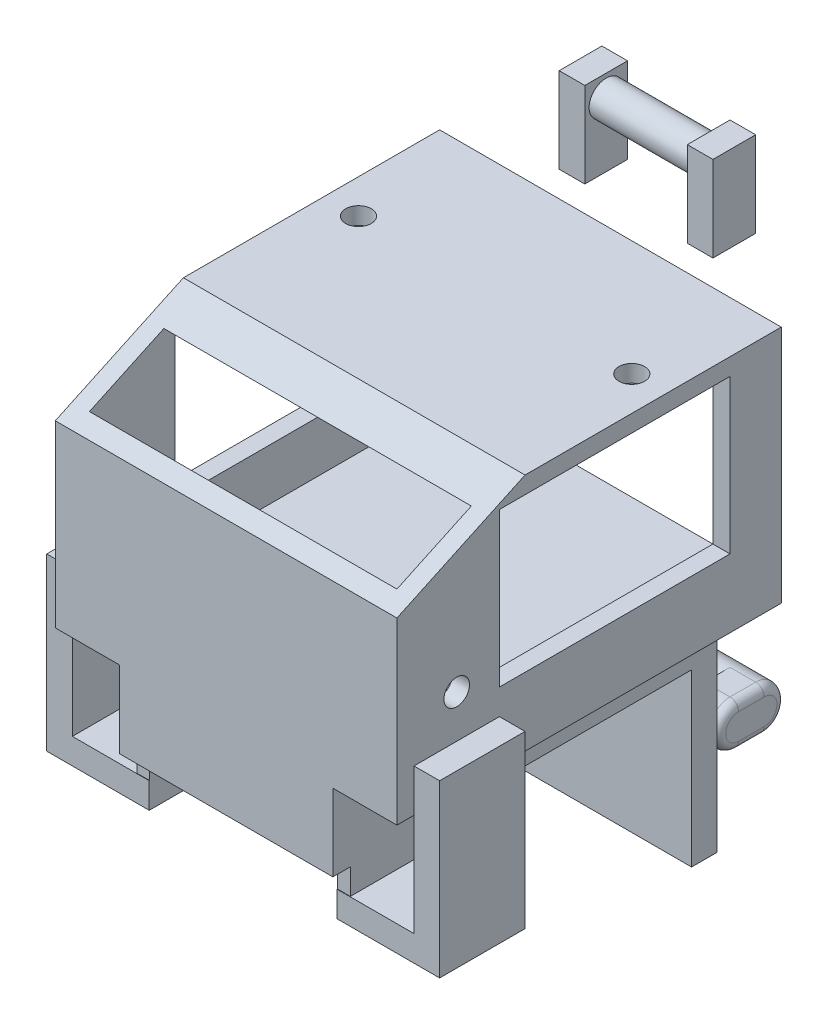
SolidWorks part; units mm, degrees
ref_plane "正面" through (0, 0, 0) normal (0, 0, 1) x (1, 0, 0)
ref_plane "平面" through (0, 0, 0) normal (0, 1, 0) x (1, 0, 0)
ref_plane "右側面" through (0, 0, 0) normal (1, 0, 0) x (0, 0, -1)
sketch "ｽｹｯﾁ1" plane through (0, 0, 0) normal (0, 1, 0) x (1, 0, 0)
  line L1 (0, 0) -> (25, 0)
  line L2 (0, 0) -> (0, 42)
  line L3 (0, 42) -> (25, 42)
  line L4 (25, 0) -> (25, 42)
  dimension "D1" = 25
  dimension "D2" = 42
extrude "ﾎﾞｽ - 押し出し1" add sketch "ｽｹｯﾁ1" along normal blind 9
sketch "ｽｹｯﾁ2" plane through (0, 0, -42) normal (0, 0, -1) x (-1, 0, 0)
  line L1 (-25, 9) -> (0, 9)
  line L2 (-25, 9) -> (-25, -20)
  line L3 (-25, -20) -> (0, -20)
  line L4 (0, 9) -> (0, -20)
  dimension "D1" = 29
extrude "ﾎﾞｽ - 押し出し2" add sketch "ｽｹｯﾁ2" along normal blind 3
sketch "ｽｹｯﾁ3" plane through (0, 9, 0) normal (0, 1, 0) x (1, 0, 0)
  line L1 (-7.5, 0) -> (32.5, 0)
  line L2 (-7.5, 0) -> (-7.5, 45)
  line L3 (-7.5, 45) -> (32.5, 45)
  line L4 (32.5, 0) -> (32.5, 45)
  line L5 (0, 0) -> (25, 0) construction
  line L6 (0, 45) -> (25, 45) construction
  line L7 (0, 45) -> (0, 0) construction
  dimension "D1" = 40
  dimension "D2" = 7.5
extrude "ﾎﾞｽ - 押し出し3" add sketch "ｽｹｯﾁ3" along normal blind 28
sketch "ｽｹｯﾁ4" plane through (0, 0, -45) normal (0, 0, -1) x (-1, 0, 0)
  line L0 (-32.5, 37) -> (7.5, 37) construction
  line L1 (5.5, 35) -> (-30.5, 35)
  line L2 (5.5, 35) -> (5.5, 11)
  line L3 (5.5, 11) -> (-30.5, 11)
  line L4 (-30.5, 35) -> (-30.5, 11)
  line L5 (7.5, 37) -> (7.5, 9) construction
  line L6 (-32.5, 37) -> (-32.5, 9) construction
  line L7 (0, 9) -> (7.5, 9) construction
  dimension "D1" = 2
  dimension "D2" = 2
  dimension "D3" = 2
  dimension "D4" = 2
extrude "ｶｯﾄ - 押し出し1" cut sketch "ｽｹｯﾁ4" against normal blind 43
sketch "ｽｹｯﾁ6" plane through (32.5, 0, 0) normal (1, 0, 0) x (0, 0, -1)
  line L0 (42, 0) -> (42, -20) construction
  line L1 (2, -6) -> (12, -6)
  line L2 (2, -6) -> (2, 14)
  line L3 (2, 14) -> (12, 14)
  line L4 (12, -6) -> (12, 14)
  line L5 (0, 9) -> (45, 9) construction
  dimension "D1" = 30
  dimension "D2" = 20
  dimension "D3" = 10
  dimension "D4" = 15
extrude "ﾎﾞｽ - 押し出し4" add sketch "ｽｹｯﾁ6" along normal blind 3
sketch "ｽｹｯﾁ7" plane through (0, -6, 0) normal (0, -1, 0) x (1, 0, 0)
  line L0 (35.5, -2) -> (32.5, -2) construction
  line L1 (32.5, -12) -> (23.5, -12)
  line L2 (32.5, -12) -> (32.5, -2)
  line L3 (32.5, -2) -> (23.5, -2)
  line L4 (23.5, -12) -> (23.5, -2)
  dimension "D1" = 9
extrude "ﾎﾞｽ - 押し出し5" add sketch "ｽｹｯﾁ7" against normal blind 3
ref_plane "平面1" through (12.5, 0, 0) normal (1, 0, 0) x (0, 0, -1)
mirror "ﾐﾗｰ1" about plane through (12.5, 0, 0) normal (1, 0, 0) of "ﾎﾞｽ - 押し出し4", "ﾎﾞｽ - 押し出し5"
sketch "ｽｹｯﾁ8" plane through (0, 37, 0) normal (0, 1, 0) x (1, 0, 0)
  line L0 (12.5, -15.95) -> (12.5, 15.95) construction
  line L1 (3.5, 53) -> (6.5, 53)
  line L2 (3.5, 53) -> (3.5, 48)
  line L3 (3.5, 48) -> (6.5, 48)
  line L4 (6.5, 53) -> (6.5, 48)
  line L5 (21.5, 48) -> (18.5, 48)
  line L6 (18.5, 53) -> (18.5, 48)
  line L7 (21.5, 53) -> (18.5, 53)
  line L8 (21.5, 53) -> (21.5, 48)
  line L10 (32.5, 45) -> (-7.5, 45) construction
  dimension "D1" = 5
  dimension "D2" = 3
  dimension "D3" = 12
  dimension "D4" = 8
extrude "ﾎﾞｽ - 押し出し6" add sketch "ｽｹｯﾁ8" along normal blind 10
sketch "ｽｹｯﾁ9" plane through (6.5, 0, 0) normal (1, 0, 0) x (0, 0, -1)
  line L0 (48, 47) -> (48, 37) construction
  line L1 (48, 47) -> (53, 47) construction
  circle A0 centre (50.5, 44.5) radius 2
  dimension "D1" = 4
  dimension "D2" = 2.5
  dimension "D3" = 2.5
extrude "ﾎﾞｽ - 押し出し7" add sketch "ｽｹｯﾁ9" along normal up to next (12 mm away)
sketch "ｽｹｯﾁ10" plane through (-7.5, 0, 0) normal (-1, 0, 0) x (0, 0, 1)
  line L0 (-2, 9) -> (0, 9) construction
  line L1 (0, 37) -> (0, 9) construction
  circle A0 centre (-7, 19) radius 1.5
  dimension "D1" = 3
  dimension "D2" = 10
  dimension "D3" = 7
extrude "ｶｯﾄ - 押し出し2" cut sketch "ｽｹｯﾁ10" against normal through all
sketch "ｽｹｯﾁ11" plane through (0, 0, -45) normal (0, 0, -1) x (-1, 0, 0)
  line L1 (-25, -20) -> (0, -20) construction
  line L2 (-12.5, 15.95) -> (-12.5, -15.95) construction
  circle A0 centre (-12.5, -10) radius 2.5
  dimension "D1" = 5
  dimension "D2" = 10
extrude "ﾎﾞｽ - 押し出し8" add sketch "ｽｹｯﾁ11" along normal blind 9
sketch "ｽｹｯﾁ12" plane through (12.5, 0, 0) normal (1, 0, 0) x (0, 0, -1)
  line L0 (45, -12.5) -> (45, -7.5) construction
  line L2 (45, -12.5) -> (54, -12.5) construction
  circle A0 centre (52, -10) radius 2.5
  dimension "D1" = 5
  dimension "D2" = 7
  dimension "D3" = 2.5
extrude "ﾎﾞｽ - 押し出し9" add sketch "ｽｹｯﾁ12" along normal blind 7
sketch "ｽｹｯﾁ13" plane through (19.5, 0, 0) normal (1, 0, 0) x (0, 0, -1)
  line L0 (52, -10) -> (49, -10) construction
  line L1 (52, -12.5) -> (49, -12.5)
  line L2 (52, -7.5) -> (49, -7.5)
  arc A0 (52, -12.5) -> (52, -7.5) centre (52, -10) ccw
  arc A1 (49, -7.5) -> (49, -12.5) centre (49, -10) ccw
  circle A2 centre (52, -10) radius 2.5 construction
  point P2 (50.5, -10)
  dimension "D1" = 2.5
  dimension "D2" = 3
extrude "ﾎﾞｽ - 押し出し10" add sketch "ｽｹｯﾁ13" along normal blind 4
fillet "ﾌｨﾚｯﾄ1" radius 1 4 edges at (23.5, -12.5, -50.5) (23.5, -10, -46.5) (23.5, -7.5, -50.5) (23.5, -10, -54.5)
mirror "ﾐﾗｰ2" about plane through (12.5, 0, 0) normal (1, 0, 0) of "ﾌｨﾚｯﾄ1", "ﾎﾞｽ - 押し出し10", "ﾎﾞｽ - 押し出し9"
sketch "ｽｹｯﾁ14" plane through (-7.5, 0, 0) normal (-1, 0, 0) x (0, 0, 1)
  line L0 (-15, 37) -> (0, 30)
  line L1 (-45, 37) -> (0, 37) construction
  line L2 (0, 37) -> (0, 9) construction
  line L3 (0, 30) -> (0, 37)
  line L4 (0, 37) -> (-15, 37)
  dimension "D1" = 15
  dimension "D2" = 7
extrude "ｶｯﾄ - 押し出し3" cut sketch "ｽｹｯﾁ14" against normal through all
sketch "ｽｹｯﾁ15" plane through (-7.5, 0, 0) normal (-1, 0, 0) x (0, 0, 1)
  line L0 (-45, 9) -> (-53, 37)
  line L1 (-53, 37) -> (-45, 37)
  line L2 (-45, 37) -> (-45, 9)
  dimension "D1" = 8
sketch "ｽｹｯﾁ19" plane through (30.5, 0, 0) normal (-1, 0, 0) x (0, 0, 1)
  line L0 (-10.7143, 35) -> (-45, 35) construction
  line L1 (-39, 17) -> (-12, 17)
  line L2 (-39, 17) -> (-39, 35)
  line L3 (-39, 35) -> (-12, 35)
  line L4 (-12, 17) -> (-12, 35)
  line L5 (-2, 30.9333) -> (-2, 11) construction
  dimension "D1" = 27
  dimension "D2" = 10
  dimension "D3" = 18
extrude "ｶｯﾄ - 押し出し5" cut sketch "ｽｹｯﾁ19" against normal through all both and the other way through all
sketch "ｽｹｯﾁ20" plane through (0, 37, 0) normal (0, 1, 0) x (1, 0, 0)
  line L0 (-7.5, 45) -> (-7.5, 15) construction
  line L1 (32.5, 15) -> (32.5, 45) construction
  line L2 (3.5, 48) -> (6.5, 48) construction
  line L3 (18.5, 48) -> (21.5, 48) construction
  circle A0 centre (-3.5, 31.5) radius 1.5
  circle A1 centre (28.5, 31.5) radius 1.5
  dimension "D1" = 3
  dimension "D2" = 3
  dimension "D3" = 4
  dimension "D4" = 4
  dimension "D5" = 16.5
  dimension "D6" = 16.5
extrude "ｶｯﾄ - 押し出し6" cut sketch "ｽｹｯﾁ20" against normal blind 10 and the other way through all
sketch "ｽｹｯﾁ21" plane through (0, 35, 0) normal (0, -1, 0) x (1, 0, 0)
  line L0 (-5.5, -45) -> (30.5, -45) construction
  line L1 (-5.5, -10.7143) -> (-5.5, -12) construction
  line L2 (22.5, -45) -> (19.5, -45)
  line L3 (22.5, -45) -> (22.5, -40)
  line L4 (22.5, -40) -> (19.5, -40)
  line L5 (19.5, -45) -> (19.5, -40)
  line L6 (5.5, -45) -> (2.5, -45)
  line L7 (5.5, -45) -> (5.5, -40)
  line L8 (5.5, -40) -> (2.5, -40)
  line L9 (2.5, -45) -> (2.5, -40)
  dimension "D1" = 3
  dimension "D2" = 5
  dimension "D3" = 3
  dimension "D4" = 5
  dimension "D5" = 8
  dimension "D6" = 8
extrude "ﾎﾞｽ - 押し出し11" add sketch "ｽｹｯﾁ21" along normal blind 10
sketch "ｽｹｯﾁ22" plane through (19.5, 0, 0) normal (-1, 0, 0) x (0, 0, 1)
  line L0 (-40, 25) -> (-45, 25) construction
  line L1 (-40, 25) -> (-40, 35) construction
  circle A0 centre (-42.5, 27.5) radius 2.5
  dimension "D1" = 5
  dimension "D2" = 2.5
  dimension "D3" = 2.5
extrude "ﾎﾞｽ - 押し出し12" add sketch "ｽｹｯﾁ22" along normal up to next
sketch "ｽｹｯﾁ23" plane through (1.5, 0, 0) normal (1, 0, 0) x (0, 0, -1)
  line L0 (42, 0) -> (0, 0) construction
  line L1 (12, -3) -> (2.0458, -3)
  line L2 (12, -3) -> (12, 0)
  line L3 (12, 0) -> (2.0458, 0)
  line L4 (2.0458, -3) -> (2.0458, 0)
extrude "ﾎﾞｽ - 押し出し13" add sketch "ｽｹｯﾁ23" against normal blind 1.5
mirror "ﾐﾗｰ3" about plane through (12.5, 0, 0) normal (1, 0, 0) of "ﾎﾞｽ - 押し出し13"
